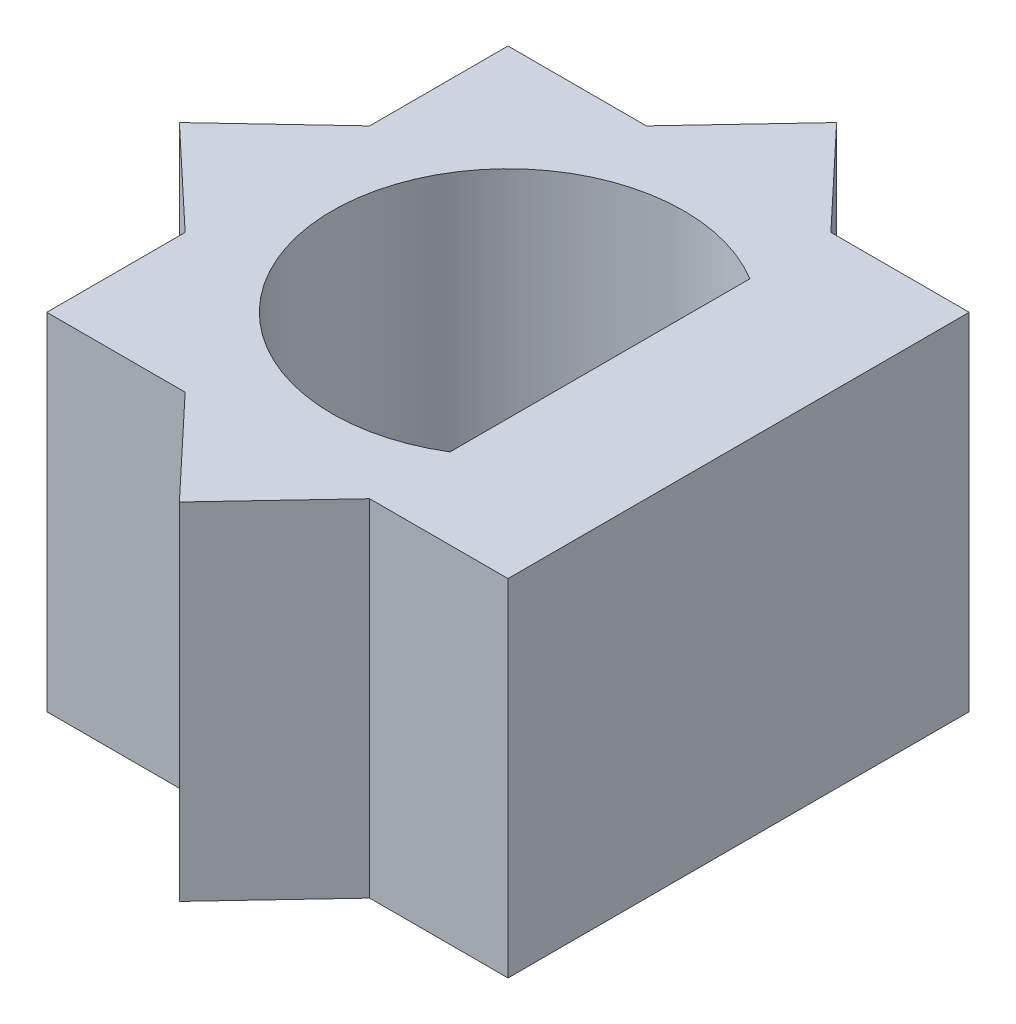
SolidWorks part; units mm, degrees
ref_plane "Plan de face" through (0, 0, 0) normal (0, 0, 1) x (1, 0, 0)
ref_plane "Plan de dessus" through (0, 0, 0) normal (0, 1, 0) x (1, 0, 0)
ref_plane "Plan de droite" through (0, 0, 0) normal (1, 0, 0) x (0, 0, -1)
sketch "Esquisse1" plane through (0, 0, 0) normal (0, 1, 0) x (1, 0, 0)
  line L0 (0, 0) -> (0, 8.5137) construction
  line L1 (-6.9598, 0) -> (8.435, 0) construction
  line L2 (1.1073, -1.1073) -> (9.4238, -9.4238) construction
  line L3 (1.1073, 1.1073) -> (-6.8521, -6.8521) construction
  line L4 (-4, 4) -> (4, 4)
  line L5 (-4, 4) -> (-4, -4)
  line L6 (4, 4) -> (4, -4)
  line L7 (-4, -4) -> (4, -4)
  line L8 (0, 5.7) -> (-1.6, 4)
  line L9 (0, 5.7) -> (1.6, 4)
  line L10 (-5.7, 0) -> (-4, 1.6)
  line L11 (-5.7, 0) -> (-4, -1.6)
  line L12 (0, -5.7) -> (-1.6, -4)
  line L13 (0, -5.7) -> (1.6, -4)
  line L16 (1.5945, 2.6) -> (1.5945, -2.6)
  circle A0 centre (0, 0) radius 3.05
  dimension "D1" = 45
  dimension "5.8" = 6.1
  dimension "D2" = 45
  dimension "D3" = 1.7
  dimension "D4" = 1.7
  dimension "D5" = 2.4
  dimension "D6" = 2.4
  dimension "D7" = 1.7
  dimension "D8" = 2.4055
  dimension "D9" = 2.4
  dimension "D10" = 8
  dimension "D11" = 2.4
  dimension "D12" = 2.4
  dimension "D14" = 2.4
  dimension "D17" = 5.2
extrude "Boss.-Extru.1" add sketch "Esquisse1" along normal blind 6
